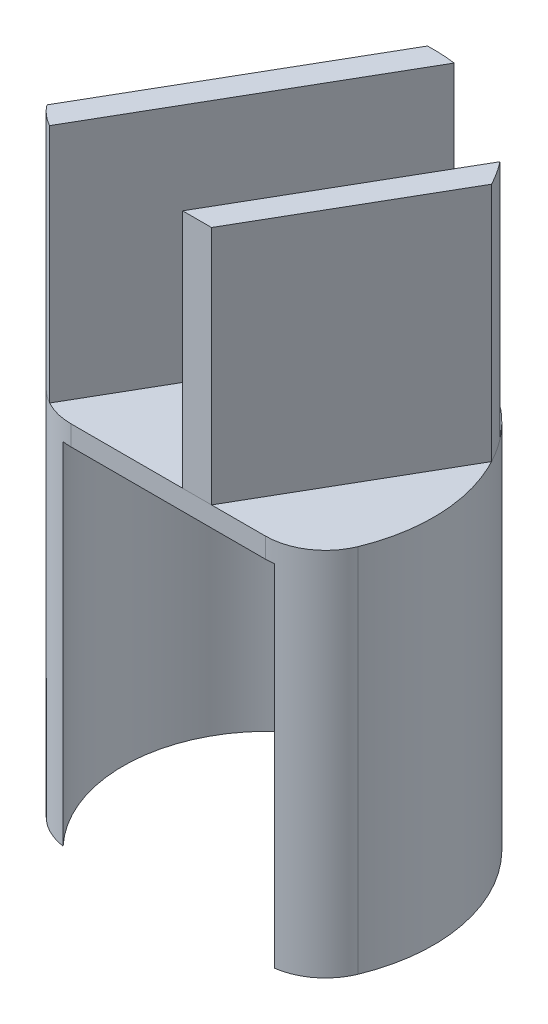
SolidWorks part; units mm, degrees
ref_plane "前视基准面" through (0, 0, 0) normal (0, 0, 1) x (1, 0, 0)
ref_plane "上视基准面" through (0, 0, 0) normal (0, 1, 0) x (1, 0, 0)
ref_plane "右视基准面" through (0, 0, 0) normal (1, 0, 0) x (0, 0, -1)
other "Configuration Table"
sketch "草图1" plane through (0, 0, 0) normal (0, 1, 0) x (1, 0, 0)
  circle A0 centre (0, 0) radius 14.5
  circle A1 centre (0, 0) radius 16.5
  dimension "D1" = 29
  dimension "D2" = 2
extrude "凸台-拉伸1" add sketch "草图1" along normal blind 35
sketch "草图3" plane through (0, 35, 0) normal (0, 1, 0) x (1, 0, 0)
  circle A1 centre (0, 0) radius 16.5
  circle A2 centre (0, 0) radius 16.5
  dimension "D1" = 0
extrude "凸台-拉伸2" add sketch "草图3" along normal blind 2
ref_plane "基准面1" through (0, 0, 10) normal (0, 0, 1) x (1, 0, 0)
sketch "草图4" plane through (0, 0, 10) normal (0, 0, 1) x (1, 0, 0)
  line L1 (-21.3332, 39.7218) -> (28.4145, 39.7218)
  line L2 (-21.3332, 39.7218) -> (-21.3332, -3.9689)
  line L3 (-21.3332, -3.9689) -> (28.4145, -3.9689)
  line L4 (28.4145, 39.7218) -> (28.4145, -3.9689)
extrude "切除-拉伸1" cut sketch "草图4" along normal through all
sketch "草图5" plane through (0, 37, 0) normal (0, 1, 0) x (1, 0, 0)
  circle A0 centre (0, 0) radius 3.75
  dimension "D1" = 7.5
extrude "切除-拉伸2" cut sketch "草图5" against normal up to next
fillet "圆角1" radius 6 2 edges at (13.1244, 18.5, 10) (-13.1244, 18.5, 10)
sketch "草图6" plane through (0, 37, 0) normal (0, 1, 0) x (1, 0, 0)
  line L0 (13.0479, 10.0996) -> (1.4434, -10)
  line L1 (-0.5833, 16.4897) -> (-14.4988, -7.6126)
  line L2 (-24.0688, -10) -> (24.0688, -10) construction
  line L3 (2.2226, 16.3496) -> (-12.5707, -9.2732)
  line L4 (14.5721, 7.7397) -> (4.3301, -10)
  line L5 (-9.7082, -10) -> (9.7082, -10) construction
  line L7 (-9.7082, -10) -> (9.7082, -10)
  line L8 (1.4434, -10) -> (4.3301, -10)
  circle A0 centre (0, 0) radius 6.25 construction
  arc A1 (-15.2558, -6.2857) -> (-9.7082, -10) centre (-9.7082, -4) ccw construction
  arc A2 (15.2558, -6.2857) -> (-15.2558, -6.2857) centre (0, 0) ccw construction
  arc A3 (2.2226, 16.3496) -> (-0.5833, 16.4897) centre (0, 0) ccw
  arc A6 (15.2558, -6.2857) -> (-15.2558, -6.2857) centre (0, 0) ccw
  arc A7 (-15.2558, -6.2857) -> (-9.7082, -10) centre (-9.7082, -4) ccw
  arc A8 (9.7082, -10) -> (15.2558, -6.2857) centre (9.7082, -4) ccw
  arc A9 (14.5721, 7.7397) -> (13.0479, 10.0996) centre (0, 0) ccw
  arc A10 (-14.4988, -7.6126) -> (-12.5707, -9.2732) centre (-9.7082, -4) ccw
  point P11 (0, 0)
  point P22 (0, 0)
  point P23 (0, 0)
  point P24 (0, 0)
  point P25 (0, 0)
  point P26 (0, 0)
  dimension "D1" = 12.5
  dimension "D2" = 60
  dimension "D3" = 2.5
  dimension "D4" = 2.5
  dimension "D5" = 0
extrude "凸台-拉伸3" add sketch "草图6" along normal blind 24 separate body
